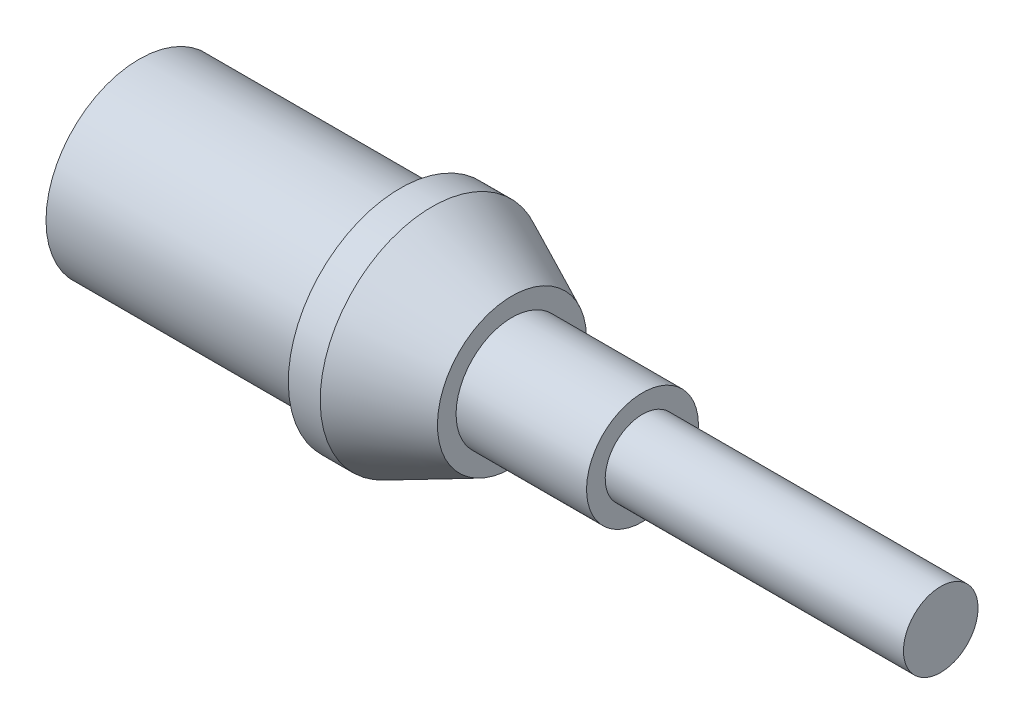
SolidWorks part; units mm, degrees
ref_plane "Plan de face" through (0, 0, 0) normal (0, 0, 1) x (1, 0, 0)
ref_plane "Plan de dessus" through (0, 0, 0) normal (0, 1, 0) x (1, 0, 0)
ref_plane "Plan de droite" through (0, 0, 0) normal (1, 0, 0) x (0, 0, -1)
sketch "Esquisse1" plane through (0, 0, 0) normal (0, 0, 1) x (1, 0, 0)
  line L0 (7, 3) -> (10, 3)
  line L1 (10, 3) -> (10, 1.5)
  line L2 (10, 1.5) -> (13.5, 1.5)
  line L3 (13.5, 1.5) -> (13.5, 1)
  line L4 (13.5, 1) -> (21.5, 1)
  line L5 (21.5, 1) -> (21.5, 0)
  line L10 (7, 3) -> (7, 2.5)
  line L12 (7, 2.5) -> (0, 2.5)
  line L13 (0, 2.5) -> (0, 0)
  line L17 (0, 0) -> (21.5, 0)
  dimension "D1" = 2.5
  dimension "D2" = 3
  dimension "D3" = 3
  dimension "D4" = 1.5
  dimension "D5" = 3.5
  dimension "D6" = 8
  dimension "D7" = 1
  dimension "D8" = 7
revolve "Révolution16" add sketch "Esquisse1" angle 360 about L17
chamfer "Chanfrein2" distance 1 angle 65 1 edges at (10, -3, 0)
